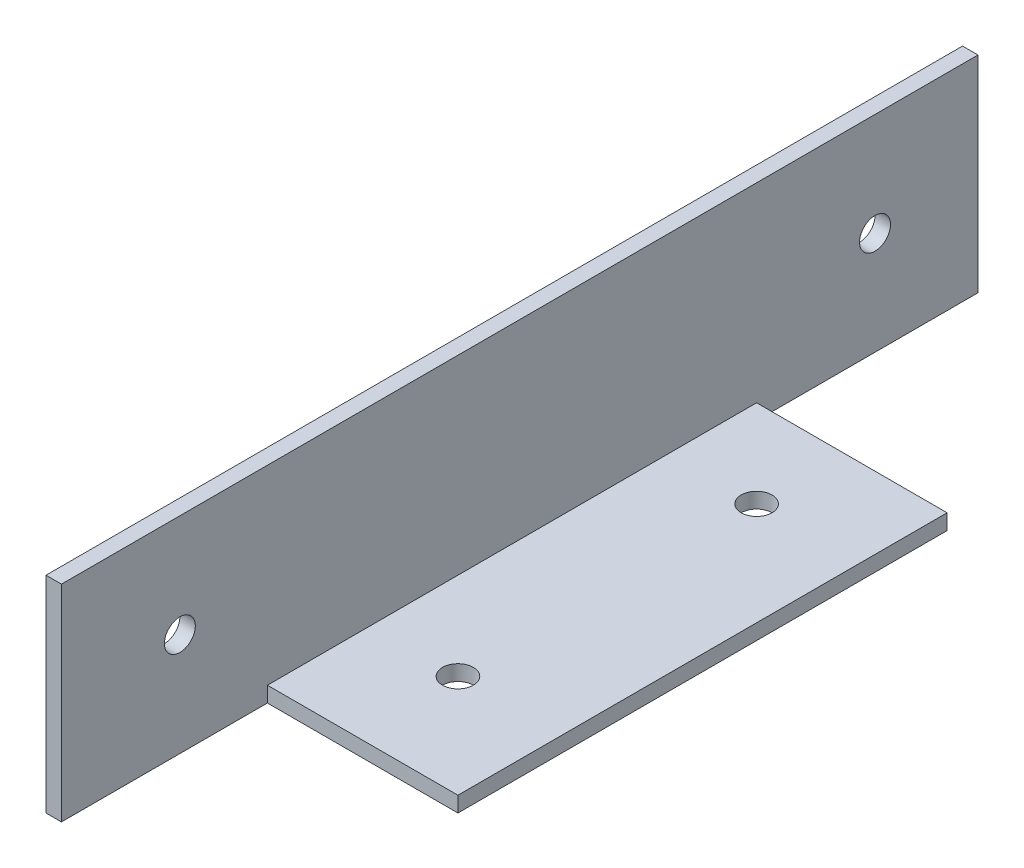
SolidWorks part; units mm, degrees
ref_plane "Plan de face" through (0, 0, 0) normal (0, 0, 1) x (1, 0, 0)
ref_plane "Plan de dessus" through (0, 0, 0) normal (0, 1, 0) x (1, 0, 0)
ref_plane "Plan de droite" through (0, 0, 0) normal (1, 0, 0) x (0, 0, -1)
sketch "Esquisse1" plane through (0, 0, 0) normal (0, 0, 1) x (1, 0, 0)
  line L0 (-24.9314, 6.5915) -> (-24.9314, -13.4085)
  line L1 (-24.9314, -13.4085) -> (-4.9314, -13.4085)
  line L2 (-4.9314, -13.4085) -> (-4.9314, -11.9085)
  line L3 (-4.9314, -11.9085) -> (-23.4314, -11.9085)
  line L4 (-23.4314, -11.9085) -> (-23.4314, 6.5915)
  line L5 (-23.4314, 6.5915) -> (-24.9314, 6.5915)
  dimension "D1" = 1.5
  dimension "D2" = 1.5
  dimension "D3" = 20
  dimension "D4" = 20
extrude "Extrusion1" add sketch "Esquisse1" along normal blind 89
sketch "Esquisse2" plane through (0, -11.9085, 0) normal (0, 1, 0) x (-1, 0, 0)
  line L0 (14.9314, 59) -> (14.9314, 30) construction
  line L1 (4.9314, 0) -> (23.4314, 0) construction
  line L2 (4.9314, 89) -> (23.4314, 89) construction
  line L3 (23.4314, 89) -> (23.4314, 0) construction
  line L4 (4.9314, 89) -> (23.4314, 89)
  line L5 (4.9314, 89) -> (4.9314, 69)
  line L6 (4.9314, 69) -> (23.4314, 69)
  line L7 (23.4314, 89) -> (23.4314, 69)
  line L8 (4.9314, 89) -> (4.9314, 0) construction
  line L9 (4.9314, 0) -> (23.4314, 0)
  line L10 (4.9314, 0) -> (4.9314, 21.5)
  line L11 (4.9314, 21.5) -> (23.4314, 21.5)
  line L12 (23.4314, 0) -> (23.4314, 21.5)
  circle A0 centre (14.9314, 59) radius 1.5
  circle A1 centre (14.9314, 30) radius 1.5
  dimension "D1" = 30
  dimension "D2" = 30
  dimension "D3" = 20
  dimension "D4" = 21.5
  dimension "D5" = 10
extrude "Extrusion2" cut sketch "Esquisse2" against normal blind 100
sketch "Esquisse3" plane through (-23.4314, 0, 0) normal (1, 0, 0) x (0, 0, -1)
  line L0 (-77.5, -3.4085) -> (-10, -3.4085) construction
  line L2 (0, -13.4085) -> (0, 6.5915) construction
  line L3 (-89, 6.5915) -> (0, 6.5915) construction
  line L4 (-89, -13.4085) -> (-89, 6.5915) construction
  circle A0 centre (-77.5, -3.4085) radius 1.5
  circle A1 centre (-10, -3.4085) radius 1.5
  dimension "D1" = 10
  dimension "D2" = 10
  dimension "D3" = 11.5
extrude "Extrusion3" cut sketch "Esquisse3" against normal blind 100
